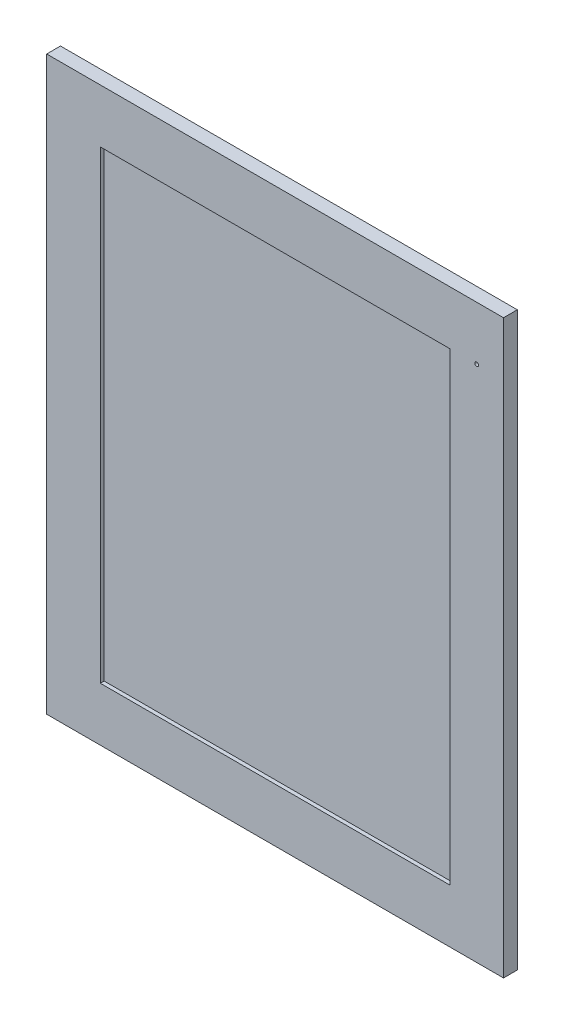
SolidWorks part; units mm, degrees
material "Acero"
ref_plane "Front Plane" through (0, 0, 0) normal (0, 0, 1) x (1, 0, 0)
ref_plane "Top Plane" through (0, 0, 0) normal (0, 1, 0) x (1, 0, 0)
ref_plane "Right Plane" through (0, 0, 0) normal (1, 0, 0) x (0, 0, -1)
ref_plane "Back Plane" through (0, 0, -18) normal (0, 0, 1) x (1, 0, 0)
ref_plane "Bottom Plane" through (0, -746, 0) normal (0, 1, 0) x (-1, 0, 0)
ref_plane "Left Plane" through (-596, 0, 0) normal (1, 0, 0) x (0, 0, -1)
sketch "Sketch1" plane through (0, 0, 0) normal (0, 0, 1) x (1, 0, 0)
  line L0 (55, -746) -> (-55, -746) construction
  line L1 (0, -746) -> (-596, -746)
  line L2 (0, -746) -> (0, 0)
  line L3 (0, 0) -> (-596, 0)
  line L4 (-596, -746) -> (-596, 0)
  line L5 (55, 0) -> (-55, 0) construction
  line L6 (-596, -55) -> (-596, 55) construction
  line L7 (0, -55) -> (0, 55) construction
extrude "Door Part" add sketch "Sketch1" against normal up to surface (18 mm away) up to plane "Back Plane"
sketch "Sketch6" plane through (0, 0, 0) normal (0, 0, 1) x (1, 0, 0)
  line L1 (0, 0) -> (-596, 0) construction
  line L3 (0, -746) -> (0, 0) construction
  circle A0 centre (-35, -70) radius 2.5
  dimension "D3" = 5
  dimension "D1" = 70
  dimension "D2" = 35
extrude "Base Single" cut sketch "Sketch6" against normal through all
ref_plane "Base Single Handle Plane 1" through (-35, 0, 0) normal (1, 0, 0) x (0, 0, -1)
ref_plane "Base Single Handle Plane 2" through (0, -70, 0) normal (0, 1, 0) x (-1, 0, 0)
sketch "Sketch7" plane through (0, 0, 0) normal (0, 0, 1) x (1, 0, 0)
  line L8 (-70, -676) -> (-70, -70)
  line L9 (-70, -70) -> (-526, -70)
  line L10 (-526, -70) -> (-526, -676)
  line L11 (-526, -676) -> (-70, -676)
  line L12 (-70, -676) -> (-70, -70)
  line L13 (-70, -70) -> (-526, -70)
  line L14 (-526, -70) -> (-526, -676)
  line L15 (-526, -676) -> (-70, -676)
  dimension "D1" = 70
extrude "Cut-Extrude1" cut sketch "Sketch7" against normal blind 5
move or copy body "Corpo-Sposta/copia1" [suppressed] bodies to move or copy 117
